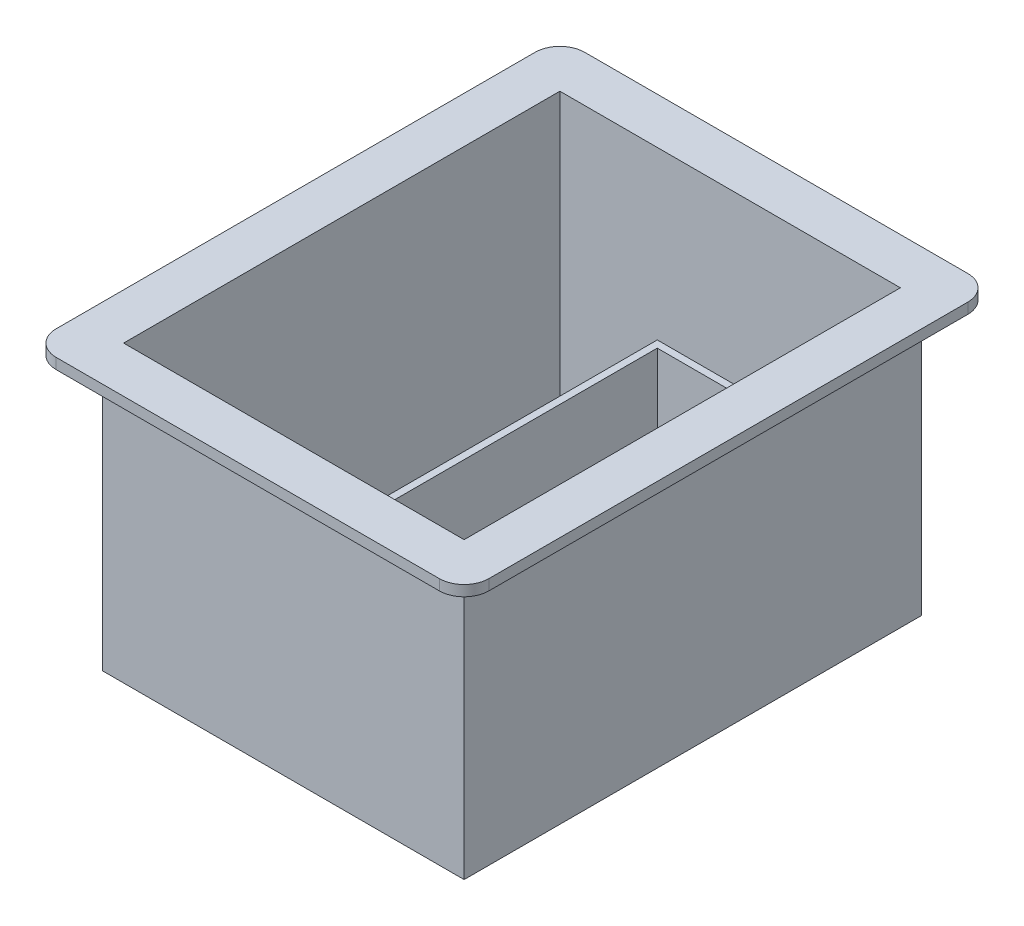
SolidWorks part; units mm, degrees
ref_plane "Front Plane" through (0, 0, 0) normal (0, 0, 1) x (1, 0, 0)
ref_plane "Top Plane" through (0, 0, 0) normal (0, 1, 0) x (1, 0, 0)
ref_plane "Right Plane" through (0, 0, 0) normal (1, 0, 0) x (0, 0, -1)
sketch "Sketch1" plane through (0, 0, 0) normal (0, 1, 0) x (1, 0, 0)
  line L1 (0, 0) -> (102, 0)
  line L2 (0, 0) -> (0, 129)
  line L3 (0, 129) -> (102, 129)
  line L4 (102, 0) -> (102, 129)
  dimension "D1" = 129
  dimension "D2" = 102
extrude "Boss-Extrude1" add sketch "Sketch1" along normal blind 77
sketch "Sketch2" plane through (0, 77, 0) normal (0, 1, 0) x (1, 0, 0)
  line L0 (0, 129) -> (0, 0) construction
  line L1 (-10, 139) -> (112, 139)
  line L2 (-10, 139) -> (-10, -10)
  line L3 (-10, -10) -> (112, -10)
  line L4 (112, 139) -> (112, -10)
  line L5 (102, 129) -> (0, 129) construction
  line L6 (102, 0) -> (102, 129) construction
  line L7 (0, 0) -> (102, 0) construction
  dimension "D1" = 10
  dimension "D2" = 10
  dimension "D3" = 10
  dimension "D4" = 10
extrude "Boss-Extrude2" add sketch "Sketch2" along normal blind 3
sketch "Sketch3" plane through (0, 80, 0) normal (0, 1, 0) x (1, 0, 0)
  line L1 (3, 126) -> (99, 126)
  line L2 (3, 126) -> (3, 3)
  line L3 (3, 3) -> (99, 3)
  line L4 (99, 126) -> (99, 3)
  line L5 (112, 64.5) -> (-10, 64.5) construction
  line L6 (112, -10) -> (112, 139) construction
  line L7 (-10, 139) -> (-10, -10) construction
  line L8 (3, 126) -> (99, 3) construction
  line L9 (99, 126) -> (3, 3) construction
  line L10 (51, 139) -> (51, -10) construction
  line L11 (112, 139) -> (-10, 139) construction
  line L12 (-10, -10) -> (112, -10) construction
  point P16 (51, 64.5)
  point P17 (51, 64.5)
  dimension "D1" = 96
  dimension "D2" = 123
extrude "Cut-Extrude1" cut sketch "Sketch3" against normal blind 77
sketch "Sketch4" plane through (0, 3, 0) normal (0, 1, 0) x (1, 0, 0)
  line L5 (30.4598, 127.5686) -> (94.4598, 127.5686)
  line L6 (30.4598, 127.5686) -> (30.4598, 38.5686)
  line L7 (30.4598, 38.5686) -> (94.4598, 38.5686)
  line L8 (94.4598, 127.5686) -> (94.4598, 38.5686)
  line L9 (3, 3) -> (65, 3)
  line L10 (3, 3) -> (3, 37)
  line L11 (3, 37) -> (65, 37)
  line L12 (65, 3) -> (65, 37)
  dimension "D1" = 62
  dimension "D2" = 34
  dimension "D3" = 64
  dimension "D4" = 89
extrude "Boss-Extrude3" add sketch "Sketch4" along normal blind 30
sketch "Sketch5" plane through (0, 33, 0) normal (0, 1, 0) x (1, 0, 0)
  line L0 (30.4598, 82.2843) -> (94.4598, 82.2843) construction
  line L1 (30.4598, 126) -> (30.4598, 38.5686) construction
  line L2 (94.4598, 38.5686) -> (94.4598, 126) construction
  line L3 (94.4598, 38.5686) -> (94.4598, 126) construction
  line L4 (32.4598, 124) -> (92.4598, 124)
  line L5 (32.4598, 124) -> (32.4598, 40.5686)
  line L6 (32.4598, 40.5686) -> (92.4598, 40.5686)
  line L7 (92.4598, 124) -> (92.4598, 40.5686)
  line L8 (32.4598, 124) -> (92.4598, 40.5686) construction
  line L9 (32.4598, 40.5686) -> (92.4598, 124) construction
  line L10 (30.4598, 38.5686) -> (94.4598, 38.5686) construction
  line L11 (65, 37) -> (3, 37) construction
  line L12 (3, 3) -> (63, 3)
  line L13 (3, 3) -> (3, 35)
  line L14 (3, 35) -> (63, 35)
  line L15 (63, 3) -> (63, 35)
  line L16 (65, 3) -> (65, 37) construction
  point P6 (62.4598, 82.2843)
  dimension "D1" = 2
  dimension "D2" = 2
  dimension "D3" = 2
  dimension "D4" = 2
extrude "Cut-Extrude2" cut sketch "Sketch5" against normal blind 30
fillet "Fillet1" radius 7 4 edges at (-10, 78.5, -139) (112, 78.5, -139) (112, 78.5, 10) (-10, 78.5, 10)
